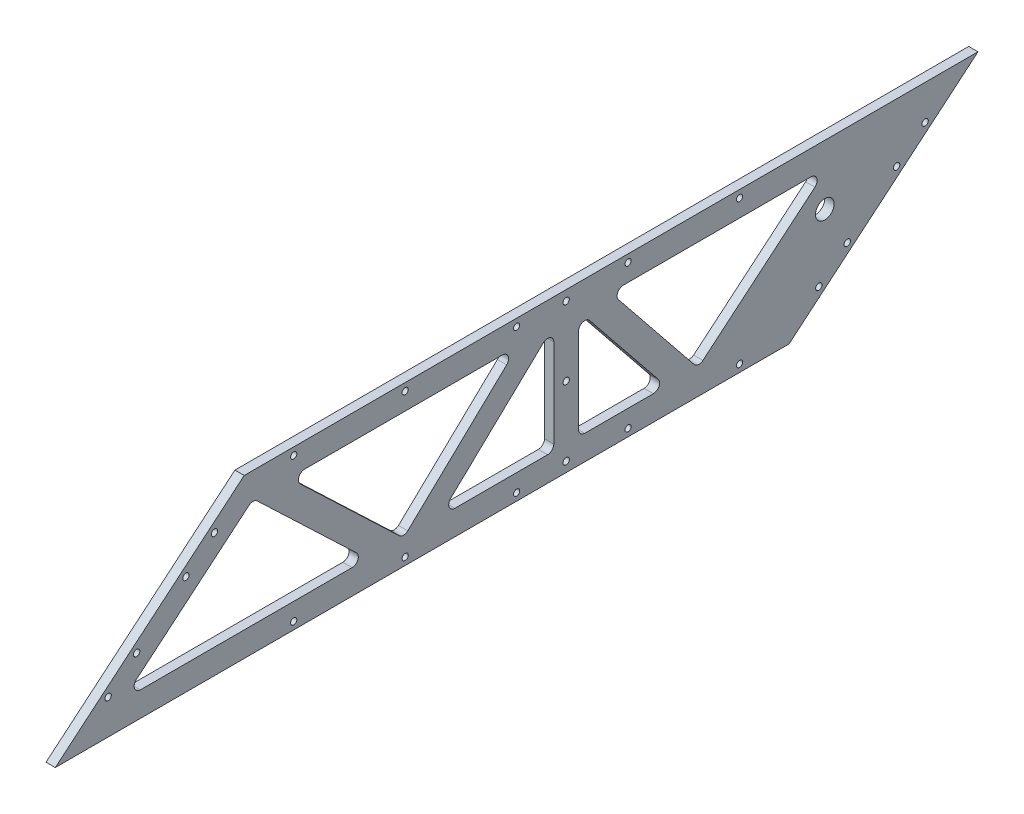
SolidWorks part; units mm, degrees
material "6061-T6 (SS)"
ref_plane "Front Plane" through (0, 0, 0) normal (0, 0, 1) x (1, 0, 0)
ref_plane "Top Plane" through (0, 0, 0) normal (0, 1, 0) x (1, 0, 0)
ref_plane "Right Plane" through (0, 0, 0) normal (1, 0, 0) x (0, 0, -1)
sketch "Sketch1" plane through (0, 0, 0) normal (1, 0, 0) x (0, 0, -1)
  line L0 (0, 12.7) -> (0, -12.7) construction
  line L1 (0, -12.7) -> (33.2976, -40.64) construction
  line L2 (33.2976, -40.64) -> (312.6976, -40.64)
  line L3 (312.6976, -40.64) -> (345.9952, -12.7)
  line L4 (345.9952, -12.7) -> (345.9952, 12.7) construction
  line L5 (345.9952, 12.7) -> (312.6976, 40.64) construction
  line L6 (312.6976, 40.64) -> (33.2976, 40.64)
  line L7 (33.2976, 40.64) -> (0, 12.7)
  line L8 (33.2976, 40.64) -> (33.2976, -40.64) construction
  line L9 (312.6976, 40.64) -> (312.6976, -40.64) construction
  line L10 (0, 0) -> (345.9952, 0) construction
  line L11 (0, 12.7) -> (-63.5681, -40.64)
  line L12 (-63.5681, -40.64) -> (33.2976, -40.64)
  line L13 (312.6976, 40.64) -> (409.5633, 40.64)
  line L14 (409.5633, 40.64) -> (345.9952, -12.7)
  point P10 (33.2976, 0)
  point P12 (312.6976, 0)
  dimension "D1" = 81.28
  dimension "D2" = 279.4
  dimension "D3" = 25.4
  dimension "D4" = 40
extrude "Boss-Extrude1" add sketch "Sketch1" along normal blind 4.7625
sketch "Sketch2" plane through (4.7625, 0, 0) normal (1, 0, 0) x (0, 0, -1)
  line L0 (-3.2177, 10) -> (373.048, 10) construction
  line L1 (312.6976, -40.64) -> (409.5633, 40.64) construction
  line L2 (345.048, 10) -> (245.048, 10) construction
  line L3 (245.048, -5) -> (345.048, -5) construction
  line L4 (245.048, -5) -> (245.048, 25) construction
  line L5 (245.048, 25) -> (345.048, 25) construction
  line L6 (345.048, -5) -> (345.048, 25) construction
  line L7 (33.2976, 40.64) -> (-63.5681, -40.64) construction
  line L9 (0, 0) -> (361.1305, 0) construction
  circle A0 centre (300.048, 10) radius 6.9977 construction
  circle A1 centre (282.2147, 8) radius 1.4986 construction
  circle A2 centre (270.2178, 15.9334) radius 0.9906 construction
  circle A3 centre (282.2147, 8) radius 11.4777 construction
  circle A4 centre (270.2178, 15.9334) radius 7.1501 construction
  circle A5 centre (300.048, 10) radius 12.827 construction
  circle A6 centre (261.048, 10) radius 14 construction
  circle A7 centre (282.2147, 8) radius 5.1181 construction
  circle A8 centre (331.0042, 10) radius 4.7625
  point P11 (300.048, 10)
  point P12 (282.2147, 8)
  point P13 (270.2178, 15.9334)
  point P23 (261.048, 10)
  dimension "D5" = 13.9954
  dimension "D6" = 2.9972
  dimension "D7" = 1.9812
  dimension "D8" = 25.654
  dimension "D9" = 22.9553
  dimension "D10" = 14.3002
  dimension "D12" = 28
  dimension "D13" = 10.2362
  dimension "D17" = 9.525
  dimension "D1" = 17.9451
  dimension "D2" = 14.3828
  dimension "D3" = 30
  dimension "D4" = 100
  dimension "D11" = 10.922
  dimension "D14" = 16
  dimension "D15" = 13
  dimension "D16" = 55
  dimension "D18" = 30.9562
  dimension "D19" = 28
  dimension "D20" = 10
extrude "Gearbox (with Press fits)" cut sketch "Sketch2" against normal through all
sketch "Sketch3" plane through (4.7625, 0, 0) normal (1, 0, 0) x (0, 0, -1)
  line L0 (0, 0) -> (361.1305, 0) construction
  line L1 (28.757, 36.83) -> (405.0227, 36.83) construction
  line L4 (33.2976, 40.64) -> (-63.5681, -40.64) construction
  line L5 (409.5633, 40.64) -> (33.2976, 40.64) construction
  line L6 (312.6976, -40.64) -> (409.5633, 40.64) construction
  circle A0 centre (287.2976, 36.83) radius 1.5811
  circle A1 centre (230.1476, 36.83) radius 1.5811
  circle A2 centre (172.9976, 36.83) radius 1.5811
  circle A3 centre (115.8476, 36.83) radius 1.5811
  circle A4 centre (58.6976, 36.83) radius 1.5812
  circle A5 centre (58.6976, -36.83) radius 1.5812
  circle A6 centre (115.8476, -36.83) radius 1.5811
  circle A7 centre (172.9976, -36.83) radius 1.5811
  circle A8 centre (230.1476, -36.83) radius 1.5811
  circle A9 centre (287.2976, -36.83) radius 1.5811
  dimension "D1" = 3.1623
  dimension "D2" = 25.4
  dimension "D4" = 3.81
  dimension "D3" = 5
extrude "Cut-Extrude1" cut sketch "Sketch3" against normal through all
hole_wizard "#4 Clearance Hole2" positions "Sketch5" profile "Sketch4" hole size "#4" standard "ANSI Inch"
sketch "Sketch5" plane through (4.7625, 0, 0) normal (1, 0, 0) x (0, 0, -1)
  line L12 (-15.1353, 0) -> (361.1305, 0) construction
  line L13 (33.2976, 40.64) -> (-63.5681, -40.64) construction
  line L14 (312.6976, -40.64) -> (409.5633, 40.64) construction
  line L17 (403.636, 40.64) -> (306.7703, -40.64) construction
  line L18 (409.5633, 40.64) -> (33.2976, 40.64) construction
  line L19 (-63.5681, -40.64) -> (312.6976, -40.64) construction
  line L21 (39.2249, 40.64) -> (-57.6408, -40.64) construction
  line L23 (382.4437, 22.8575) -> (18.0326, 22.8575) construction
  line L25 (367.8505, 10.6124) -> (3.4394, 10.6124) construction
  line L27 (342.5558, -10.6124) -> (-21.8554, -10.6124) construction
  line L29 (327.9626, -22.8575) -> (-36.4485, -22.8575) construction
  line L31 (355.2032, 0) -> (0, 0) construction
  point P60 (327.9626, -22.8575)
  point P62 (342.5558, -10.6124)
  point P64 (367.8505, 10.6124)
  point P66 (382.4437, 22.8575)
  point P75 (18.0326, 22.8575)
  point P79 (3.4394, 10.6124)
  point P83 (-21.8554, -10.6124)
  point P87 (-36.4485, -22.8575)
  dimension "D1" = 19.05
  dimension "D2" = 19.05
  dimension "D3" = 16.51
  dimension "D4" = 16.51
  dimension "D5" = 3.81
  dimension "D6" = 3.81
sketch "Sketch4" plane through (4.7625, -22.8575, -327.9626) normal (0, 1, 0) x (0, 0, -1)
  line L0 (0, 0) -> (0, 29.6826)
  line L1 (0, 29.6826) -> (1.6319, 28.702)
  line L2 (1.6319, 28.702) -> (1.6319, 0)
  line L5 (1.6319, 0) -> (0, 0)
  line L10 (0, 29.6826) -> (-1.632, 28.702) construction
  line L11 (0, -6.35) -> (0, 107.95) construction
  dimension "Hole Dia." = 3.2639
  dimension "Hole Depth" = 28.702
  dimension "Drill Angle" = 118
hole_wizard "#4 Clearance Hole1" positions "Sketch10" profile "Sketch8" hole size "#4" standard "ANSI Inch"
sketch "Sketch10" plane through (4.7625, 0, 0) normal (1, 0, 0) x (0, 0, -1)
  line L0 (27.2435, 35.56) -> (403.5092, 35.56) construction
  line L1 (33.2976, 40.64) -> (-63.5681, -40.64) construction
  line L3 (312.6976, -40.64) -> (409.5633, 40.64) construction
  line L4 (-15.1353, 0) -> (361.1305, 0) construction
  line L6 (409.5633, 40.64) -> (33.2976, 40.64) construction
  line L7 (198.3976, 35.56) -> (198.3976, -35.56) construction
  point P16 (198.3976, 35.56)
  point P19 (198.3976, -35.56)
  point P24 (198.3976, 0)
  dimension "D1" = 5.08
  dimension "D2" = 165.1
sketch "Sketch8" plane through (4.7625, 35.56, -198.3976) normal (0, 1, 0) x (0, 0, -1)
  line L0 (0, 0) -> (0, 5.8066)
  line L1 (0, 5.8066) -> (1.6319, 4.826)
  line L2 (1.6319, 4.826) -> (1.6319, 0)
  line L5 (1.6319, 0) -> (0, 0)
  line L10 (0, 5.8066) -> (-1.6319, 4.826) construction
  line L11 (0, -6.35) -> (0, 107.95) construction
  dimension "Hole Dia." = 3.2639
  dimension "Hole Depth" = 4.826
  dimension "Drill Angle" = 118
sketch "Sketch11" plane through (4.7625, 0, 0) normal (1, 0, 0) x (0, 0, -1)
  line L0 (18.1623, 27.94) -> (394.4281, 27.94) construction
  line L1 (33.2976, 40.64) -> (-63.5681, -40.64) construction
  line L2 (312.6976, -40.64) -> (409.5633, 40.64) construction
  line L3 (-48.4329, -27.94) -> (327.8329, -27.94) construction
  line L4 (-21.9928, -22.3328) -> (35.7449, 26.1148)
  line L5 (39.9758, 25.9814) -> (90.8271, -22.4663)
  line L6 (88.637, -27.94) -> (-19.9519, -27.94)
  line L7 (62.0768, 22.4663) -> (112.7937, -25.8534)
  line L8 (117.1739, -25.8534) -> (167.8909, 22.4663)
  line L9 (165.7008, 27.94) -> (64.2668, 27.94)
  line L10 (186.6825, 22.8285) -> (139.1405, -22.4663)
  line L11 (141.3306, -27.94) -> (188.8726, -27.94)
  line L12 (192.0476, -24.765) -> (192.0476, 20.5298)
  line L13 (204.7476, 18.9322) -> (204.7476, -24.765)
  line L14 (409.5633, 40.64) -> (33.2976, 40.64) construction
  line L15 (-63.5681, -40.64) -> (312.6976, -40.64) construction
  line L16 (207.9226, -27.94) -> (243.0966, -27.94)
  line L17 (245.5699, -22.7741) -> (210.3959, 20.9231)
  line L18 (225.2091, 22.7741) -> (263.9995, -25.4158)
  line L19 (268.5136, -25.8571) -> (325.9442, 22.3328)
  line L20 (323.9033, 27.94) -> (227.6824, 27.94)
  line L21 (114.9838, 27.94) -> (114.9838, -27.94) construction
  circle A0 centre (198.3976, 0) radius 6.35 construction
  arc A1 (188.8726, -27.94) -> (192.0476, -24.765) centre (188.8726, -24.765) ccw
  arc A2 (139.1405, -22.4663) -> (141.3306, -27.94) centre (141.3306, -24.765) ccw
  arc A3 (192.0476, 20.5298) -> (186.6825, 22.8285) centre (188.8726, 20.5298) ccw
  arc A4 (167.8909, 22.4663) -> (165.7008, 27.94) centre (165.7008, 24.765) ccw
  arc A5 (62.0768, 22.4663) -> (64.2668, 27.94) centre (64.2668, 24.765) cw
  arc A6 (112.7937, -25.8534) -> (117.1739, -25.8534) centre (114.9838, -23.5547) ccw
  arc A7 (90.8271, -22.4663) -> (88.637, -27.94) centre (88.637, -24.765) cw
  arc A8 (35.7449, 26.1148) -> (39.9758, 25.9814) centre (37.7857, 23.6826) cw
  arc A9 (-21.9928, -22.3328) -> (-19.9519, -27.94) centre (-19.9519, -24.765) ccw
  circle A10 centre (331.0042, 10) radius 12.7 construction
  arc A11 (325.9442, 22.3328) -> (323.9033, 27.94) centre (323.9033, 24.765) ccw
  arc A12 (225.2091, 22.7741) -> (227.6824, 27.94) centre (227.6824, 24.765) cw
  arc A13 (263.9995, -25.4158) -> (268.5136, -25.8571) centre (266.4728, -23.4249) ccw
  arc A14 (243.0966, -27.94) -> (245.5699, -22.7741) centre (243.0966, -24.765) ccw
  arc A15 (204.7476, -24.765) -> (207.9226, -27.94) centre (207.9226, -24.765) ccw
  arc A16 (204.7476, 18.9322) -> (210.3959, 20.9231) centre (207.9226, 18.9322) cw
  point P26 (192.0476, -27.94)
  point P29 (133.3952, -27.94)
  point P32 (192.0476, 27.94)
  point P35 (173.6362, 27.94)
  point P38 (56.3315, 27.94)
  point P41 (114.9838, -27.94)
  point P44 (96.5724, -27.94)
  point P47 (37.92, 27.94)
  point P50 (-28.6752, -27.94)
  point P62 (332.6266, 27.94)
  point P65 (221.0509, 27.94)
  point P68 (266.0314, -27.94)
  point P71 (249.7281, -27.94)
  point P74 (204.7476, -27.94)
  point P77 (204.7476, 27.94)
  dimension "D3" = 12.7
  dimension "D7" = 3.175
  dimension "D9" = 25.4
  dimension "D10" = 3.175
  dimension "D1" = 12.7
  dimension "D2" = 12.7
  dimension "D4" = 12.7
  dimension "D5" = 12.7
  dimension "D6" = 12.7
  dimension "D8" = 12.7
extrude "Cut-Extrude2" cut sketch "Sketch11" against normal through all
